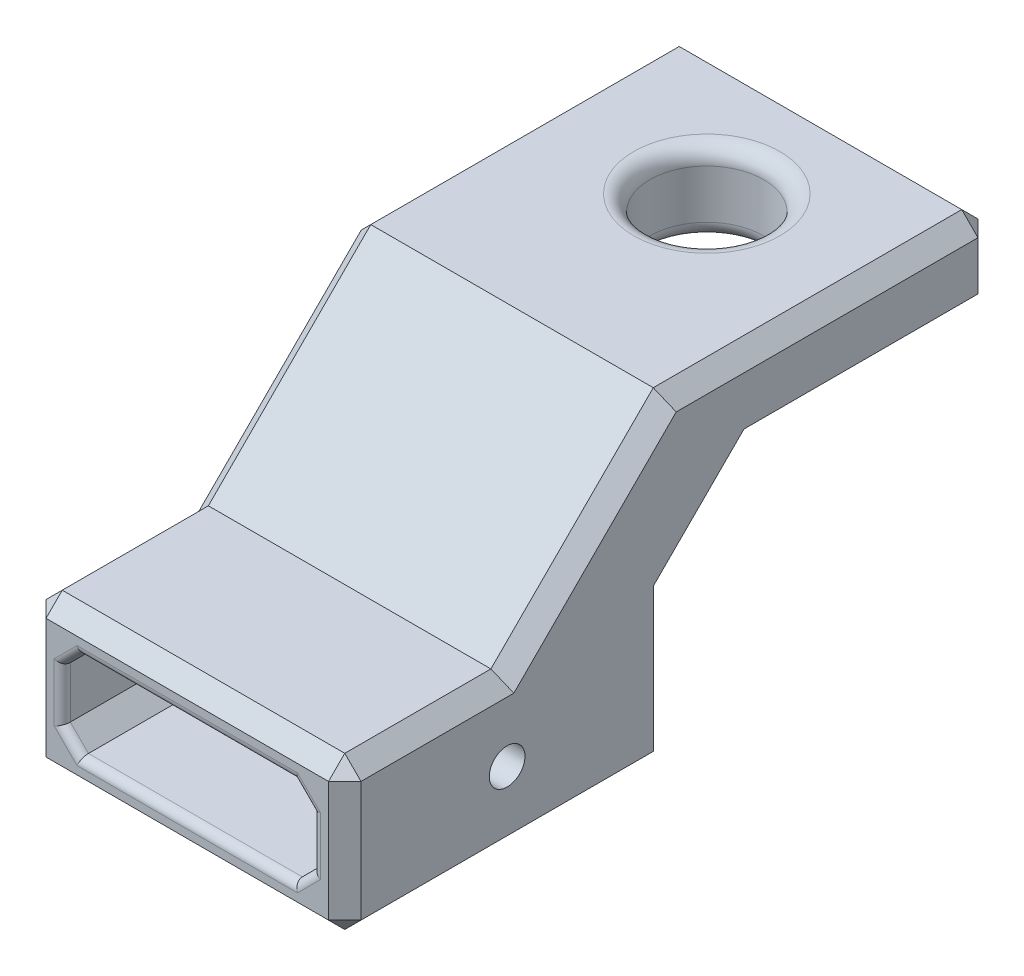
SolidWorks part; units mm, degrees
ref_plane "Plano frontal" through (0, 0, 0) normal (0, 0, 1) x (1, 0, 0)
ref_plane "Plano superior" through (0, 0, 0) normal (0, 1, 0) x (1, 0, 0)
ref_plane "Plano direito" through (0, 0, 0) normal (1, 0, 0) x (0, 0, -1)
sketch "Esboço1" plane through (0, 0, 0) normal (0, 0, 1) x (1, 0, 0)
  line L0 (15, 3) -> (14, 4) construction
  line L1 (15, 3) -> (15, 0) construction
  line L2 (14, -1) -> (15, 0) construction
  line L3 (14, -1) -> (1, -1) construction
  line L4 (0, 0) -> (1, -1) construction
  line L5 (0, 0) -> (0, 3) construction
  line L6 (1, 4) -> (0, 3) construction
  line L7 (1, 4) -> (14, 4) construction
sketch "Esboço2" plane through (0, 0, 0) normal (0, 0, 1) x (1, 0, 0)
  line L39 (-2.2, 6.2) -> (17.2, 6.2)
  line L40 (-2.2, 6.2) -> (-2.2, -3.2)
  line L41 (-2.2, -3.2) -> (17.2, -3.2)
  line L42 (17.2, 6.2) -> (17.2, -3.2)
  line L46 (15.2, 3.0828) -> (14.0828, 4.2)
  line L47 (15.2, -0.0828) -> (15.2, 3.0828)
  line L48 (14.0828, -1.2) -> (15.2, -0.0828)
  line L49 (0.9172, -1.2) -> (14.0828, -1.2)
  line L50 (-0.2, -0.0828) -> (0.9172, -1.2)
  line L51 (-0.2, 3.0828) -> (-0.2, -0.0828)
  line L52 (0.9172, 4.2) -> (-0.2, 3.0828)
  line L53 (14.0828, 4.2) -> (0.9172, 4.2)
  line L54 (15.2, 3.0828) -> (14.0828, 4.2)
  line L55 (15.2, -0.0828) -> (15.2, 3.0828)
  line L56 (14.0828, -1.2) -> (15.2, -0.0828)
  line L57 (0.9172, -1.2) -> (14.0828, -1.2)
  line L58 (-0.2, -0.0828) -> (0.9172, -1.2)
  line L59 (-0.2, 3.0828) -> (-0.2, -0.0828)
  line L60 (0.9172, 4.2) -> (-0.2, 3.0828)
  line L61 (14.0828, 4.2) -> (0.9172, 4.2)
  dimension "D2" = 2
  dimension "D3" = 2
  dimension "D4" = 2
  dimension "D5" = 2
  dimension "D1" = 0.2
extrude "Ressalto-extrusão1" add sketch "Esboço2" along normal blind 20
ref_plane "Plano1" through (-2.2, 0, 0) normal (1, 0, 0) x (0, 0, -1)
sketch "Esboço4" plane through (-2.2, 0, 0) normal (1, 0, 0) x (0, 0, -1)
  line L0 (0, 6.2) -> (5, 11.2)
  line L1 (5, 11.2) -> (20, 11.2)
  line L2 (20, 11.2) -> (20, 16.2)
  line L4 (0, 16.2) -> (-10, 6.2)
  line L5 (-20, 6.2) -> (0, 6.2) construction
  line L7 (0, 16.2) -> (20, 16.2)
  line L13 (-10, 6.2) -> (0, 6.2)
  dimension "D1" = 15
  dimension "D2" = 10
  dimension "D3" = 135
  dimension "D4" = 5
  dimension "D5" = 135
  dimension "D6" = 5
extrude "Ressalto-extrusão2" add sketch "Esboço4" along normal up to surface (19.4 mm away) contours L4 L13 L0 L1 L2 L7 up to face at (17.2, 1.5, 10)
chamfer "Chanfro2" distance 1 angle 45 23 edges at (17.2, 13.7, -20) (-2.2, 13.7, -20) (7.5, 11.2, -20) (7.5, 16.2, -20) (17.2, 11.2, -12.5) (-2.2, 11.2, -12.5) (17.2, 8.7, -2.5) (-2.2, 8.7, -2.5) (17.2, 16.2, -10) (-2.2, 16.2, -10) (17.2, 11.2, 5) (-2.2, 11.2, 5) (7.5, -3.2, 0) (-2.2, 1.5, 0) (-2.2, -3.2, 10) (-2.2, 1.5, 20) (7.5, -3.2, 20) (17.2, 1.5, 0) (17.2, -3.2, 10) (17.2, 1.5, 20) (-2.2, 6.2, 15) (7.5, 6.2, 20) (17.2, 6.2, 15)
sketch "Esboço5" plane through (0, 11.2, 0) normal (0, -1, 0) x (1, 0, 0)
  line L0 (-1.2, -19) -> (16.2, -5) construction
  circle A0 centre (7.5, -12) radius 3.5
  dimension "D1" = 7
extrude "Corte-extrusão1" cut sketch "Esboço5" against normal blind 20 contours A0
fillet "Filete1" radius 1 2 edges at (7.5, 11.2, -15.5) (7.5, 16.2, -8.5)
fillet "Filete2" radius 0.5 16 edges at (14.6414, -0.6414, 20) (14.6414, 3.6414, 20) (15.2, 1.5, 20) (7.5, -1.2, 20) (0.3586, -0.6414, 20) (-0.2, 1.5, 20) (0.3586, 3.6414, 20) (7.5, 4.2, 20) (0.3586, 3.6414, 0) (-0.2, 1.5, 0) (0.3586, -0.6414, 0) (7.5, -1.2, 0) (14.6414, -0.6414, 0) (15.2, 1.5, 0) (14.6414, 3.6414, 0) (7.5, 4.2, 0)
sketch "Esboço6" plane through (17.2, 0, 0) normal (1, 0, 0) x (0, 0, -1)
  line L0 (-19, 1.5) -> (-1, 1.5) construction
  line L1 (-19, 5.2) -> (-19, -2.2) construction
  line L2 (-1, -2.2) -> (-1, 6.6142) construction
  circle A0 centre (-10, 1.5) radius 1.1
  dimension "D1" = 2.2
extrude "Corte-extrusão2" cut sketch "Esboço6" against normal blind 10
